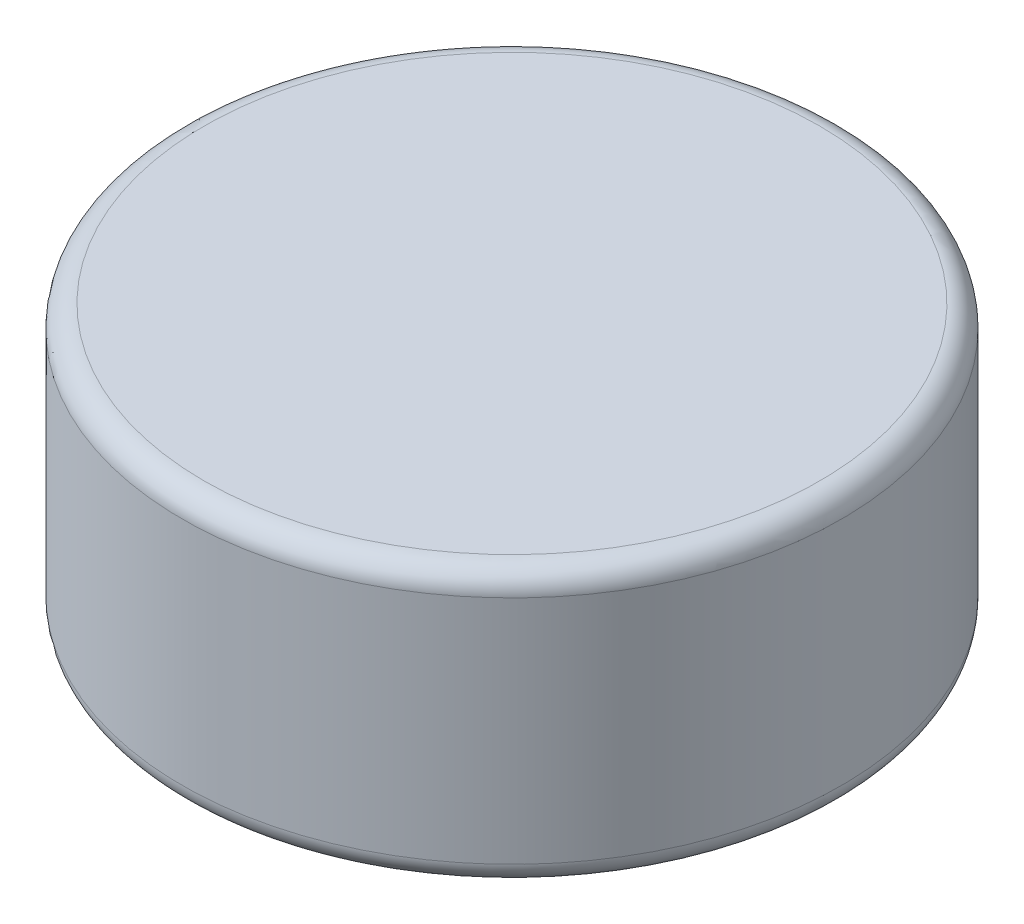
SolidWorks part; units mm, degrees
material "201 Annealed Stainless Steel (SS)"
ref_plane "Front Plane" through (0, 0, 0) normal (0, 0, 1) x (1, 0, 0)
ref_plane "Top Plane" through (0, 0, 0) normal (0, 1, 0) x (1, 0, 0)
ref_plane "Right Plane" through (0, 0, 0) normal (1, 0, 0) x (0, 0, -1)
sketch "Sketch1" plane through (0, 0, 0) normal (0, 0, 1) x (1, 0, 0)
  line L0 (2.8, 1.25) -> (0, 1.25)
  line L1 (0, 1.25) -> (0, -1.25)
  line L2 (0, -1.25) -> (2.8, -1.25)
  line L3 (3, -1.05) -> (3, 1.05)
  line L4 (0, 1.25) -> (0, -1.25) construction
  arc A0 (2.8, -1.25) -> (3, -1.05) centre (2.8, -1.05) ccw
  arc A1 (3, 1.05) -> (2.8, 1.25) centre (2.8, 1.05) ccw
revolve "Revolve1" add sketch "Sketch1" angle 360 about L4
